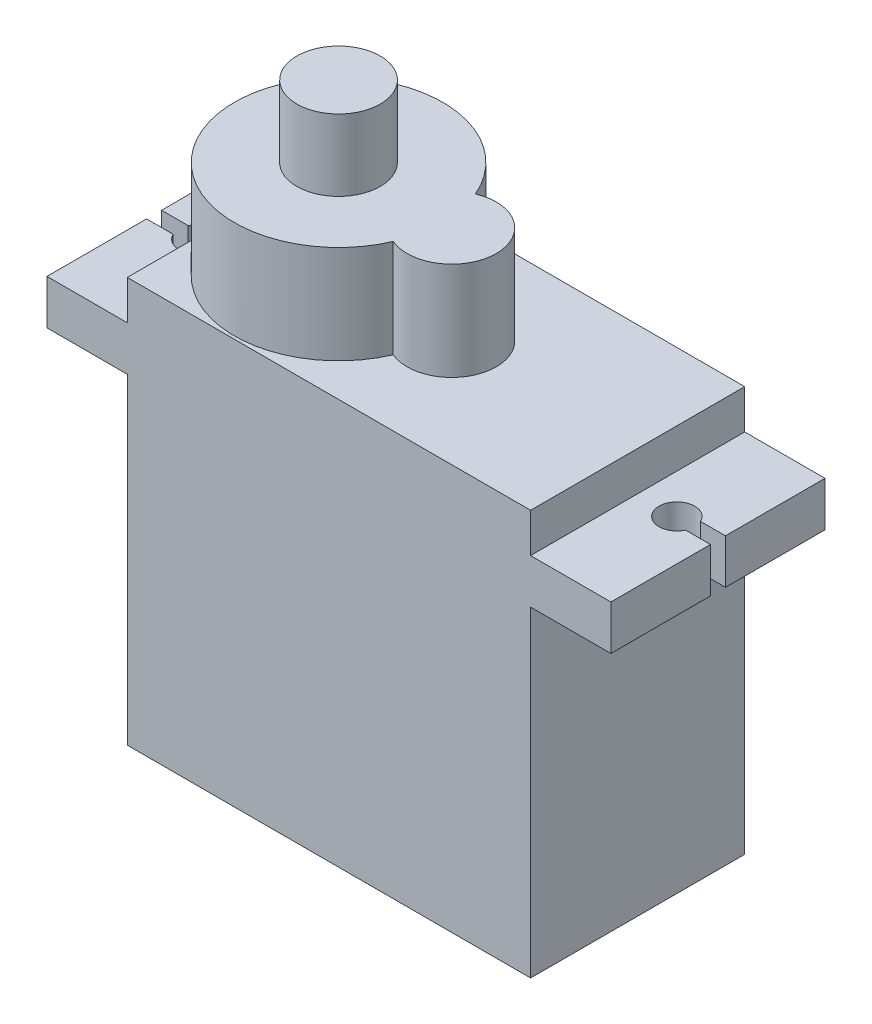
SolidWorks part; units mm, degrees
ref_plane "Front Plane" through (0, 0, 0) normal (0, 0, 1) x (1, 0, 0)
ref_plane "Top Plane" through (0, 0, 0) normal (0, 1, 0) x (1, 0, 0)
ref_plane "Right Plane" through (0, 0, 0) normal (1, 0, 0) x (0, 0, -1)
sketch "Sketch1" plane through (0, 0, 0) normal (0, 1, 0) x (1, 0, 0)
  line L1 (-46.1955, 4.7431) -> (-23.5955, 4.7431)
  line L2 (-46.1955, 4.7431) -> (-46.1955, -7.2569)
  line L3 (-46.1955, -7.2569) -> (-23.5955, -7.2569)
  line L4 (-23.5955, 4.7431) -> (-23.5955, -7.2569)
extrude "Boss-Extrude1" add sketch "Sketch1" along normal blind 22.7
ref_plane "Plane1" through (-23.5955, 22.7, -4.7431) normal (0, -1, 0) x (1, 0, 0)
sketch "Sketch2" plane through (-23.5955, 22.7, -4.7431) normal (0, -1, 0) x (1, 0, 0)
ref_plane "Plane2" through (-46.1955, 22.7, -4.7431) normal (0, 0, 1) x (1, 0, 0)
sketch "Sketch3" plane through (-46.1955, 22.7, -4.7431) normal (0, 0, 1) x (1, 0, 0)
sketch "Sketch4" plane through (0, 22.7, 0) normal (0, 1, 0) x (-1, 0, 0)
  line L0 (46.1955, 1.2569) -> (40.3555, 1.2569)
  line L1 (46.1955, -4.7431) -> (46.1955, 7.2569) construction
  circle A0 centre (40.3555, 1.2569) radius 5.84
extrude "Boss-Extrude6" add sketch "Sketch4" along normal blind 5.5
sketch "Sketch12" plane through (0, 28.2, 0) normal (0, 1, 0) x (-1, 0, 0)
  circle A0 centre (40.3555, 1.2569) radius 2.335
extrude "Boss-Extrude7" add sketch "Sketch12" along normal blind 4
sketch "Sketch13" plane through (0, 22.7, 0) normal (0, 1, 0) x (-1, 0, 0)
  line L0 (34.5155, 1.2569) -> (34.0155, 1.2569)
  circle A0 centre (40.3555, 1.2569) radius 5.84 construction
  circle A1 centre (34.0155, 1.2569) radius 2.5
extrude "Boss-Extrude8" add sketch "Sketch13" along normal blind 5.5
sketch "Sketch14" plane through (-23.5955, 0, 0) normal (1, 0, 0) x (0, 0, -1)
  line L0 (-7.2569, 22.7) -> (-7.2569, 20.5)
  line L1 (-7.2569, 22.7) -> (-7.2569, 0) construction
  line L2 (4.7431, 22.7) -> (4.7431, 0) construction
  line L3 (-7.2569, 20.5) -> (4.7431, 20.5)
  line L4 (-7.2569, 20.5) -> (-7.2569, 18)
  line L5 (-7.2569, 18) -> (4.7431, 18)
  line L6 (4.7431, 20.5) -> (4.7431, 18)
  line L7 (-7.2569, 0) -> (4.7431, 0) construction
  line L8 (-7.2569, 22.7) -> (4.7431, 22.7) construction
  line M2 (4.7431, 0) -> (4.7431, 22.7)
  line M4 (-7.2569, 22.7) -> (-7.2569, 0)
  dimension "D3" = 2.2
extrude "Boss-Extrude10" add sketch "Sketch14" along normal blind 4.5 contours L5 L3 M4 M2
sketch "Sketch15" plane through (0, 20.5, 0) normal (0, 1, 0) x (-1, 0, 0)
  line L0 (19.0955, 7.2569) -> (19.0955, -4.7431) construction
  line L1 (19.0955, 1.2569) -> (20.5955, 1.2569)
  line L2 (19.0955, 1.6769) -> (19.0955, 0.8369)
  line L3 (19.0955, 0.8369) -> (20.5955, 0.8369)
  line L4 (50.6955, 1.2569) -> (48.3955, 1.2569)
  line L5 (20.5955, 1.6769) -> (20.5955, 0.8369)
  line L6 (19.0955, 1.6769) -> (20.5955, 1.6769)
  line L7 (19.0955, 1.2569) -> (21.3955, 1.2569)
  circle A0 centre (21.3955, 1.2569) radius 1
  circle A1 centre (48.3955, 1.2569) radius 1
extrude "Cut-Extrude3" cut sketch "Sketch15" along direction (0, 1, 0) on the side against the normal through all
sketch "Sketch16" plane through (-46.1955, 0, 0) normal (-1, 0, 0) x (0, 0, 1)
  line L0 (7.2569, 24.5) -> (7.2569, 20.5)
  line L1 (7.2569, 22.7) -> (7.2569, 0) construction
  line L2 (7.2569, 20.5) -> (7.2569, 18)
  line L3 (7.2569, 20.5) -> (-4.7431, 20.5)
  line L4 (-4.7431, 22.7) -> (-4.7431, 0) construction
  line L5 (7.2569, 18) -> (-4.7431, 18)
  line L6 (-4.7431, 0) -> (7.2569, 0) construction
  line L7 (-4.7431, 22.7) -> (1.2569, 22.7) construction
  line M2 (7.2569, 0) -> (7.2569, 22.7)
  line M5 (-4.7431, 22.7) -> (-4.7431, 0)
  dimension "D3" = 2.2
extrude "Boss-Extrude11" add sketch "Sketch16" along normal blind 4.5 contours L5 L3 M2 M5
sketch "Sketch17" plane through (0, 20.5, 0) normal (0, 1, 0) x (-1, 0, 0)
  line L0 (50.6955, 0.8369) -> (50.6955, 1.6769)
  line L1 (50.6955, 1.2569) -> (49.1955, 1.2569)
  line L2 (50.6955, 1.6769) -> (49.1955, 1.6769)
  line L3 (49.1955, 0.8369) -> (49.1955, 1.6769)
  line L4 (50.6955, 7.2569) -> (50.6955, -4.7431) construction
  line L5 (50.6955, 0.8369) -> (49.1955, 0.8369)
  line L6 (50.6955, 1.2569) -> (48.2955, 1.2569)
  circle A0 centre (48.2955, 1.2569) radius 1
extrude "Cut-Extrude4" cut sketch "Sketch17" along direction (0, -1, 0) on the side against the normal through all
